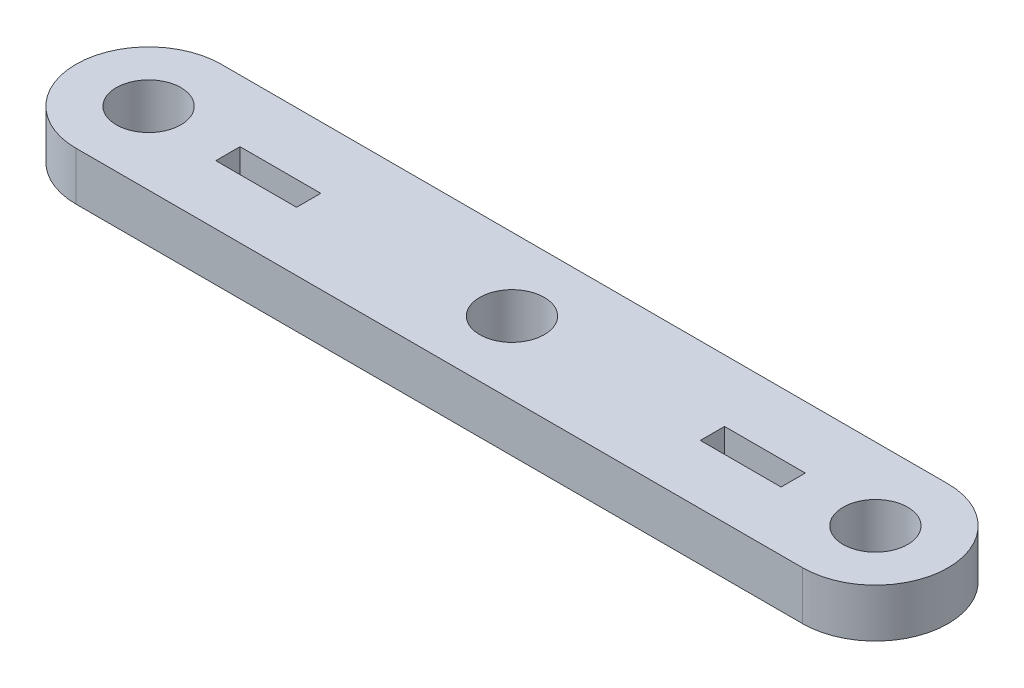
SolidWorks part; units mm, degrees
ref_plane "Front Plane" through (0, 0, 0) normal (0, 0, 1) x (1, 0, 0)
ref_plane "Top Plane" through (0, 0, 0) normal (0, 1, 0) x (1, 0, 0)
ref_plane "Right Plane" through (0, 0, 0) normal (1, 0, 0) x (0, 0, -1)
sketch "Sketch2" plane through (0, 0, 0) normal (0, 1, 0) x (1, 0, 0)
  line L1 (0, 0) -> (90, 0)
  line L3 (0, 18) -> (90, 18)
  arc A1 (0, 0) -> (0, 18) centre (0, 9) cw
  arc A2 (90, 0) -> (90, 18) centre (90, 9) ccw
  dimension "D1" = 18
  dimension "D2" = 90
extrude "Boss-Extrude1" add sketch "Sketch2" along normal blind 6
sketch "Sketch3" plane through (0, 0, 0) normal (0, -1, 0) x (1, 0, 0)
  line L0 (0, 0) -> (90, 0) construction
  line L1 (45, 0) -> (45, -18) construction
  line L2 (90, -18) -> (0, -18) construction
  circle A0 centre (0, -9) radius 4
  circle A2 centre (90, -9) radius 4
  circle A3 centre (45, -9) radius 4
  dimension "D1" = 9
  dimension "D2" = 8
extrude "Cut-Extrude1" cut sketch "Sketch3" against normal blind 6
sketch "Sketch4" plane through (0, 6, 0) normal (0, 1, 0) x (1, 0, 0)
  line L0 (45, 18) -> (45, 0) construction
  line L1 (10, 10.3213) -> (20, 10.3213)
  line L2 (10, 10.3213) -> (10, 7.3213)
  line L3 (10, 7.3213) -> (20, 7.3213)
  line L4 (20, 10.3213) -> (20, 7.3213)
  line L5 (90, 18) -> (0, 18) construction
  line L6 (0, 0) -> (90, 0) construction
  line L7 (80, 7.3213) -> (70, 7.3213)
  line L8 (70, 10.3213) -> (70, 7.3213)
  line L9 (80, 10.3213) -> (70, 10.3213)
  line L10 (80, 10.3213) -> (80, 7.3213)
  circle A0 centre (0, 9) radius 4 construction
  dimension "D3" = 10
  dimension "D1" = 3
  dimension "D2" = 10
extrude "Cut-Extrude2" cut sketch "Sketch4" against normal blind 6
